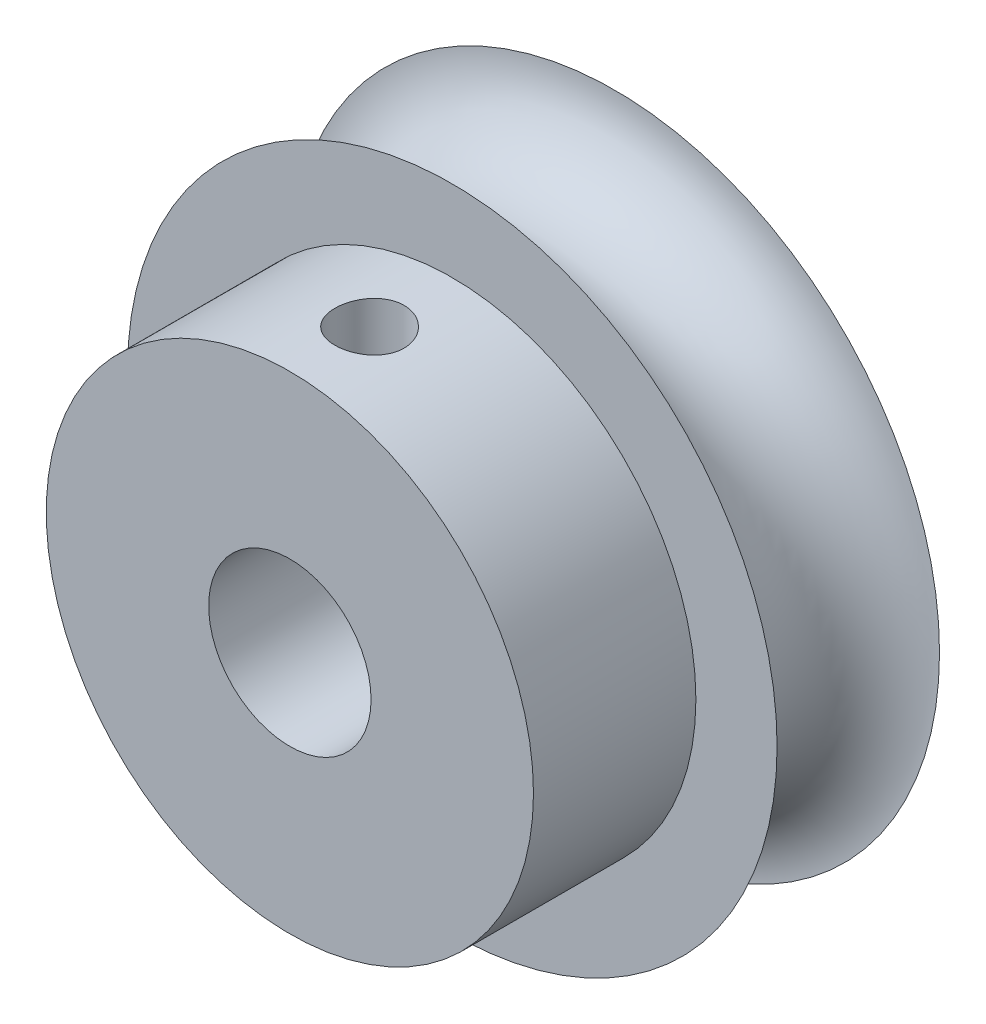
SolidWorks part; units mm, degrees
ref_plane "Front Plane" through (0, 0, 0) normal (0, 0, 1) x (1, 0, 0)
ref_plane "Top Plane" through (0, 0, 0) normal (0, 1, 0) x (1, 0, 0)
ref_plane "Right Plane" through (0, 0, 0) normal (1, 0, 0) x (0, 0, -1)
sketch "Sketch1" plane through (0, 0, 0) normal (0, 0, 1) x (1, 0, 0)
  circle A0 centre (0, 0) radius 12.7
extrude "Boss-Extrude1" add sketch "Sketch1" along normal blind 6.35
sketch "Sketch2" plane through (0, 0, 6.35) normal (0, 0, 1) x (1, 0, 0)
  circle A0 centre (0, 0) radius 9.525
extrude "Boss-Extrude2" add sketch "Sketch2" along normal blind 6.35
sketch "Sketch3" plane through (0, 0, 12.7) normal (0, 0, 1) x (1, 0, 0)
  circle A0 centre (0, 0) radius 3.175
extrude "Cut-Extrude1" cut sketch "Sketch3" against normal blind 12.7
sketch "Sketch4" plane through (0, 0, 0) normal (0, 1, 0) x (1, 0, 0)
  line L0 (12.7, 0) -> (12.7, -6.35)
  line L1 (0, 3.5759) -> (0, -14.3879) construction
  arc A0 (12.7, 0) -> (12.7, -6.35) centre (12.7, -3.175) ccw
revolve "Cut-Revolve1" cut sketch "Sketch4" angle 360 about L1
sketch "Sketch5" plane through (0, 0, 0) normal (0, 1, 0) x (1, 0, 0)
  circle A0 centre (0, -9.525) radius 1.8986
hole_wizard "#6-32 Tapped Hole1" positions "3DSketch1" profile "Sketch6" tap size "#6-32" standard "Ansi Inch"
sketch3d "3DSketch1"
  point P0 (0, 9.525, 9.584)
  point P10 (0, 0, 0)
sketch "Sketch6" plane through (0, 9.525, 9.584) normal (0, 0, 1) x (-1, 0, 0)
  line L0 (0, 0) -> (0, 10.3367)
  line L1 (0, 10.3367) -> (1.3525, 9.524)
  line L2 (1.3525, 9.524) -> (1.3525, 0)
  line L5 (1.3525, 0) -> (0, 0)
  line L10 (0, 10.3367) -> (-1.3526, 9.524) construction
  line L11 (0, -6.35) -> (0, 107.95) construction
  dimension "Tap Drill Dia." = 2.7051
  dimension "Tap Drill Depth" = 9.524
  dimension "Drill Angle" = 118
cosmetic thread "Hole Thread1" parameters "D1"=6.6525, "D2"=3.5052
